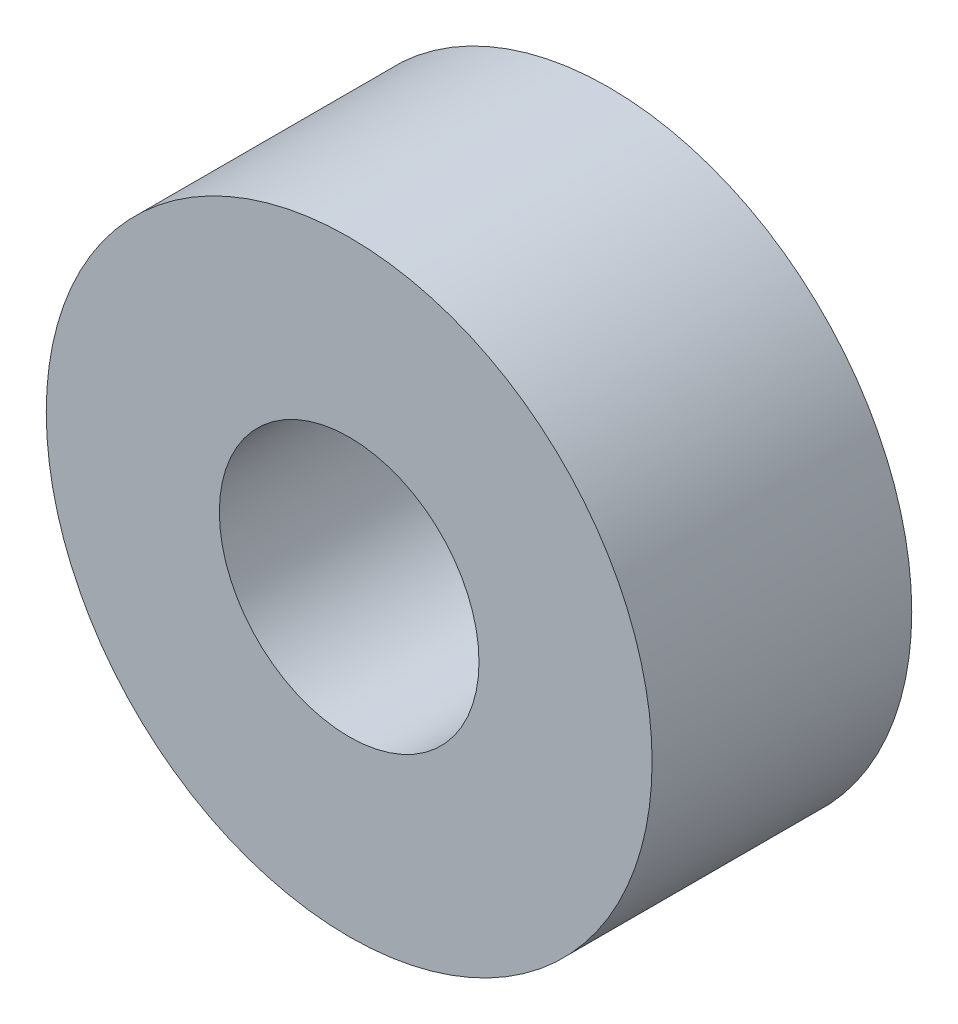
SolidWorks part; units mm, degrees
ref_plane "Piano frontale" through (0, 0, 0) normal (0, 0, 1) x (1, 0, 0)
ref_plane "Piano superiore" through (0, 0, 0) normal (0, 1, 0) x (1, 0, 0)
ref_plane "Piano destro" through (0, 0, 0) normal (1, 0, 0) x (0, 0, -1)
sketch "Schizzo1" plane through (0, 0, 0) normal (0, 0, 1) x (1, 0, 0)
  circle A0 centre (0, 0) radius 35
  circle A1 centre (0, 0) radius 15
  dimension "D1" = 30
  dimension "D2" = 70
extrude "Estrusione-Estrusione1" add sketch "Schizzo1" along normal blind 30
